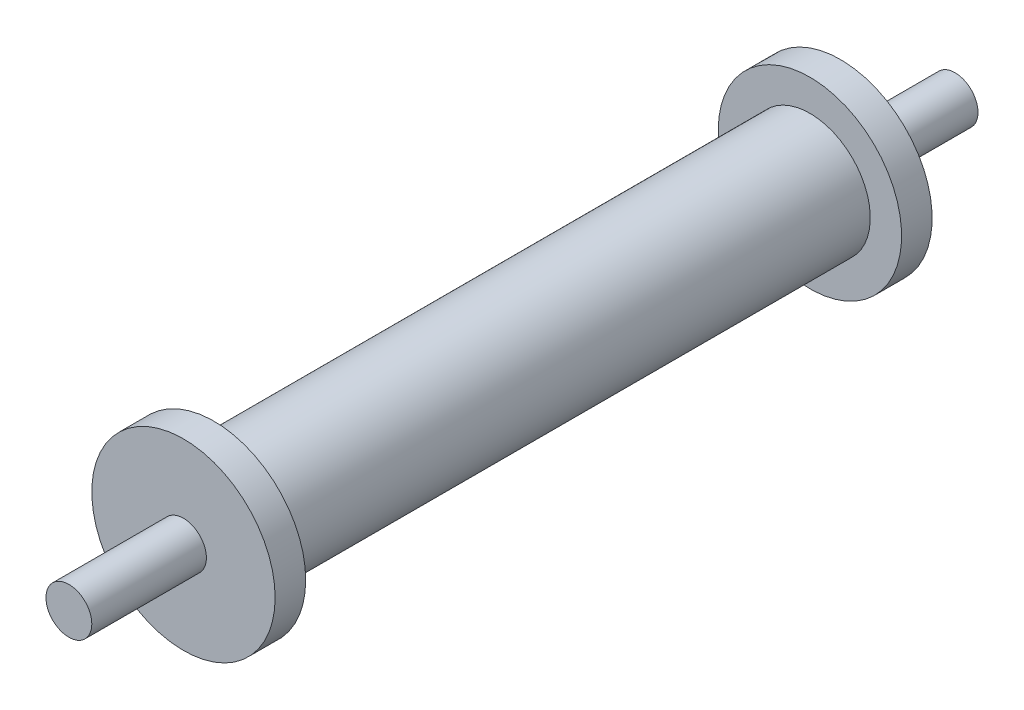
SolidWorks part; units mm, degrees
ref_plane "Ön Düzlem" through (0, 0, 0) normal (0, 0, 1) x (1, 0, 0)
ref_plane "Üst Düzlem" through (0, 0, 0) normal (0, 1, 0) x (1, 0, 0)
ref_plane "Sağ Düzlem" through (0, 0, 0) normal (1, 0, 0) x (0, 0, -1)
sketch "Sketch1" plane through (0, 0, 0) normal (0, 0, 1) x (1, 0, 0)
  circle A0 centre (0, 0) radius 3.95
  dimension "D1" = 7.9
extrude "Boss-Extrude1" add sketch "Sketch1" along normal blind 58
ref_plane "Plane1" through (0, 0, 50.5) normal (0, 0, 1) x (1, 0, 0)
sketch "Sketch2" plane through (0, 0, 50.5) normal (0, 0, 1) x (1, 0, 0)
  circle A0 centre (0, 0) radius 6
  dimension "D1" = 12
extrude "Boss-Extrude2" add sketch "Sketch2" against normal blind 2
ref_plane "Plane2" through (0, 0, 7.5) normal (0, 0, -1) x (-1, 0, 0)
sketch "Sketch3" plane through (0, 0, 7.5) normal (0, 0, -1) x (-1, 0, 0)
  circle A0 centre (0, 0) radius 6
  dimension "D1" = 12
extrude "Boss-Extrude3" add sketch "Sketch3" against normal blind 2
sketch "Sketch4" plane through (0, 0, 50.5) normal (0, 0, 1) x (1, 0, 0)
  circle A0 centre (0, 0) radius 1.5
  circle A1 centre (0, 0) radius 4.3072
  dimension "D1" = 3
extrude "Cut-Extrude1" cut sketch "Sketch4" along normal blind 10
sketch "Sketch5" plane through (0, 0, 7.5) normal (0, 0, -1) x (-1, 0, 0)
  circle A0 centre (0, 0) radius 1.5
  circle A1 centre (0, 0) radius 5.1807
  dimension "D1" = 3
extrude "Cut-Extrude2" cut sketch "Sketch5" along normal blind 10
